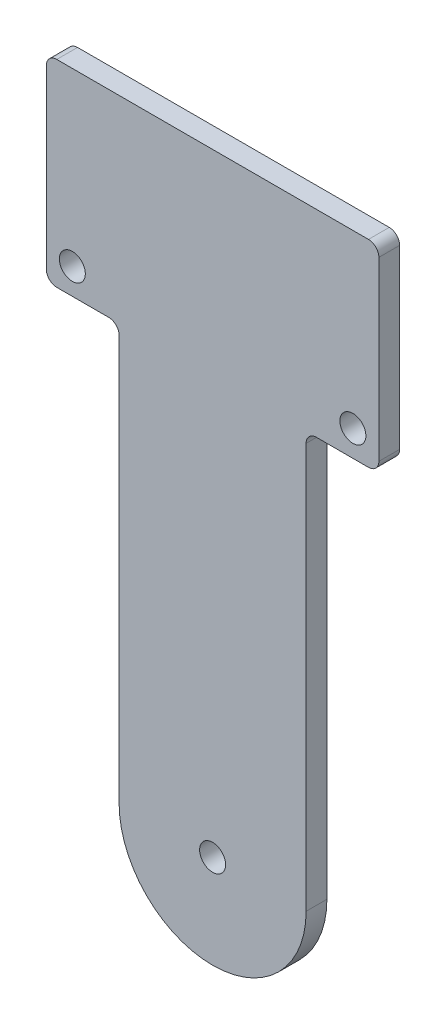
SolidWorks part; units mm, degrees
material "自訂玻璃纖維"
ref_plane "前基準面" through (0, 0, 0) normal (0, 0, 1) x (1, 0, 0)
ref_plane "上基準面" through (0, 0, 0) normal (0, 1, 0) x (1, 0, 0)
ref_plane "右基準面" through (0, 0, 0) normal (1, 0, 0) x (0, 0, -1)
sketch "草圖1" plane through (0, 0, 0) normal (0, 0, 1) x (1, 0, 0)
  line L0 (23.0486, -20.4042) -> (18.0486, -20.4042)
  line L1 (-7.9514, -2.4042) -> (-7.9514, -15.4042)
  line L2 (24.0486, -15.4042) -> (24.0486, -2.4042)
  line L3 (24.0486, -15.4042) -> (24.0486, -19.4042)
  line L4 (-7.9514, -15.4042) -> (-7.9514, -19.4042)
  line L5 (17.0486, -21.4042) -> (17.0486, -60.4042)
  line L6 (-0.9514, -60.4042) -> (-0.9514, -21.4042)
  line L7 (23.0486, -1.4042) -> (-6.9514, -1.4042)
  line L8 (-1.9514, -20.4042) -> (-6.9514, -20.4042)
  circle A0 centre (-5.4514, -17.9042) radius 1.25
  circle A1 centre (21.5486, -17.9042) radius 1.25
  arc A2 (-6.9514, -1.4042) -> (-7.9514, -2.4042) centre (-6.9514, -2.4042) ccw
  arc A3 (23.0486, -1.4042) -> (24.0486, -2.4042) centre (23.0486, -2.4042) cw
  arc A4 (17.0486, -60.4042) -> (-0.9514, -60.4042) centre (8.0486, -60.4042) cw
  arc A5 (-6.9514, -20.4042) -> (-7.9514, -19.4042) centre (-6.9514, -19.4042) cw
  arc A6 (-0.9514, -21.4042) -> (-1.9514, -20.4042) centre (-1.9514, -21.4042) ccw
  arc A7 (17.0486, -21.4042) -> (18.0486, -20.4042) centre (18.0486, -21.4042) cw
  arc A8 (23.0486, -20.4042) -> (24.0486, -19.4042) centre (23.0486, -19.4042) ccw
  circle A11 centre (8.0486, -60.4042) radius 1.25
  point P21 (-0.9514, -20.4042)
  point P26 (-1.2443, -20.6971)
  point P27 (17.3415, -20.6971)
  point P31 (8.0486, -60.4042)
  dimension "D3" = 16.5
  dimension "D4" = 16.5
  dimension "D5" = 27
  dimension "D7" = 2.5
  dimension "D10" = 39
  dimension "D11" = 2.5
  dimension "D2" = 1
  dimension "D8" = 9
  dimension "D9" = 1
  dimension "D6" = 13
extrude "填料-伸長1" add sketch "草圖1" along normal blind 2
